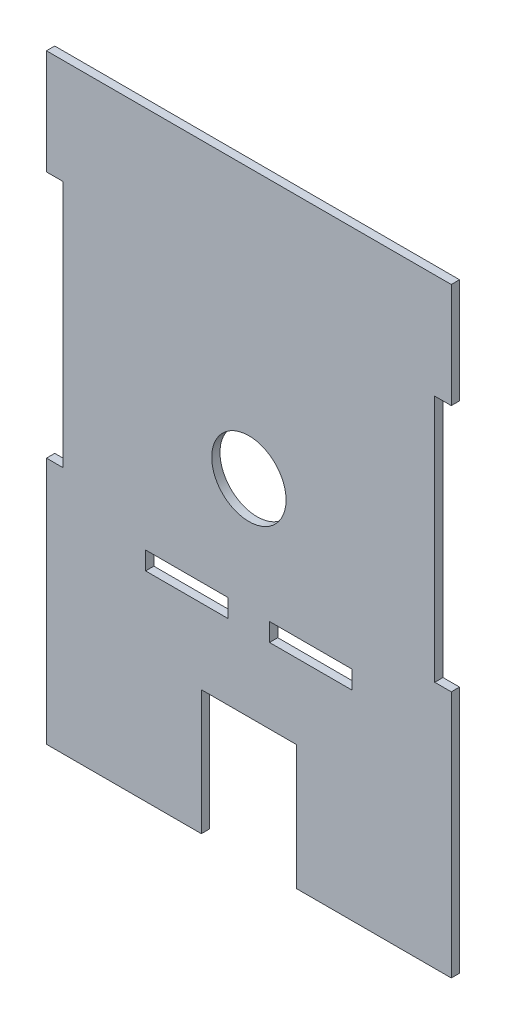
SolidWorks part; units mm, degrees
ref_plane "前视基准面" through (0, 0, 0) normal (0, 0, 1) x (1, 0, 0)
ref_plane "上视基准面" through (0, 0, 0) normal (0, 1, 0) x (1, 0, 0)
ref_plane "右视基准面" through (0, 0, 0) normal (1, 0, 0) x (0, 0, -1)
sketch "Model" plane through (0, 0, 0) normal (0, 0, 1) x (1, 0, 0)
  line L0 (4.282, 3.6522) -> (4.282, 33.6522)
  line L1 (53.282, 33.6522) -> (53.282, 3.6522)
  line L2 (51.282, 63.6522) -> (51.282, 33.6522)
  line L3 (53.282, 76.3539) -> (53.282, 63.6522)
  line L4 (53.282, 63.6522) -> (51.282, 63.6522)
  line L5 (53.282, 33.6522) -> (51.282, 33.6522)
  line L6 (6.282, 63.6522) -> (6.282, 33.6522)
  line L7 (4.282, 63.6522) -> (6.282, 63.6522)
  line L8 (4.282, 33.6522) -> (6.282, 33.6522)
  line L9 (28.782, 18.7522) -> (23.032, 18.7522)
  line L10 (23.032, 18.7522) -> (23.032, 3.6522)
  line L11 (34.532, 3.6522) -> (34.532, 18.7522)
  line L12 (34.532, 18.7522) -> (28.782, 18.7522)
  line L13 (53.282, 3.6522) -> (34.532, 3.6522)
  line L14 (23.032, 3.6522) -> (4.282, 3.6522)
  line L15 (41.282, 27.8253) -> (41.282, 30.0253)
  line L16 (31.282, 27.8253) -> (31.282, 30.0253)
  line L17 (26.282, 27.8253) -> (26.282, 30.0253)
  line L18 (16.282, 27.8253) -> (16.282, 30.0253)
  line L19 (41.282, 30.0253) -> (31.282, 30.0253)
  line L20 (31.282, 27.8253) -> (41.282, 27.8253)
  line L21 (26.282, 30.0253) -> (16.282, 30.0253)
  line L22 (26.282, 27.8253) -> (16.282, 27.8253)
  line L23 (4.282, 76.3539) -> (53.282, 76.3539)
  line L24 (4.282, 76.3539) -> (4.282, 63.6522)
  circle A0 centre (28.782, 43.7522) radius 4.5
extrude "凸台-拉伸1" add sketch "Model" along normal blind 1
